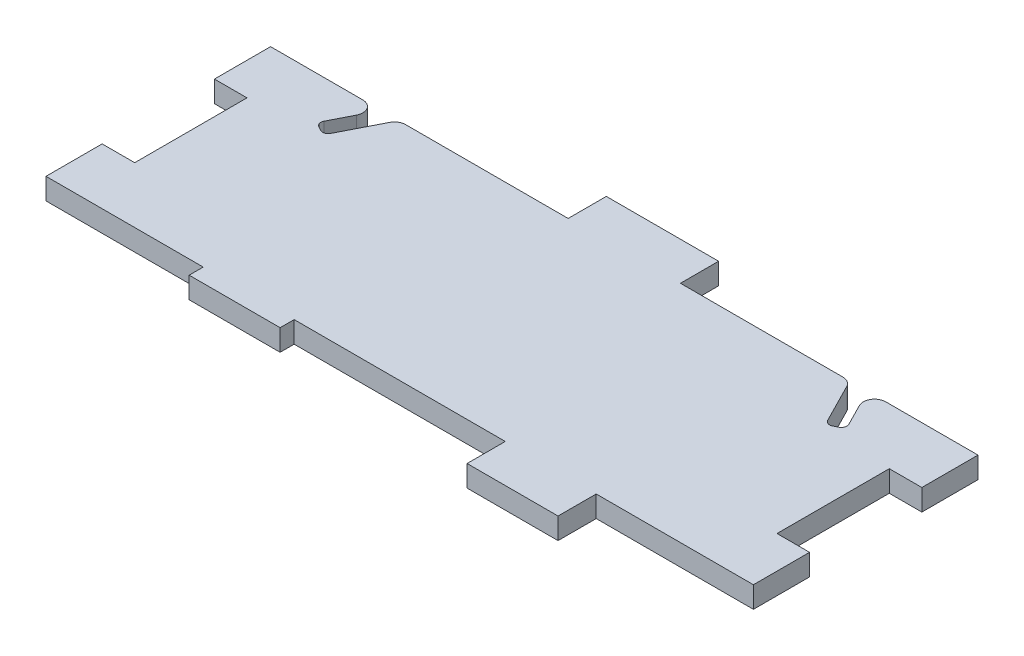
SolidWorks part; units mm, degrees
ref_plane "Front Plane" through (0, 0, 0) normal (0, 0, 1) x (1, 0, 0)
ref_plane "Top Plane" through (0, 0, 0) normal (0, 1, 0) x (1, 0, 0)
ref_plane "Right Plane" through (0, 0, 0) normal (1, 0, 0) x (0, 0, -1)
sketch "Sketch1" plane through (0, 0, 0) normal (0, 1, 0) x (1, 0, 0)
  line L0 (0, -40.8326) -> (0, -51.7928) construction
  line L1 (-80.01, 25.4) -> (-55.0009, 25.4)
  line L2 (-80.01, 25.4) -> (-80.01, 12.7)
  line L3 (-80.01, -25.4) -> (-44.45, -25.4)
  line L4 (80.01, 25.4) -> (80.01, 12.7)
  line L5 (-80.01, 25.4) -> (80.01, -25.4) construction
  line L6 (-80.01, -25.4) -> (80.01, 25.4) construction
  line L8 (-44.45, -25.4) -> (-44.45, -28.575)
  line L9 (-44.45, -28.575) -> (-23.876, -28.575)
  line L10 (-23.876, -25.4) -> (-23.876, -28.575)
  line L11 (23.876, -25.4) -> (23.876, -34.036)
  line L12 (44.45, -34.036) -> (23.876, -34.036)
  line L13 (44.45, -25.4) -> (44.45, -34.036)
  line L14 (-23.876, -25.4) -> (23.876, -25.4)
  line L15 (44.45, -25.4) -> (80.01, -25.4)
  line L16 (80.01, 12.7) -> (72.644, 12.7)
  line L17 (-80.01, 12.7) -> (-72.644, 12.7)
  line L19 (-80.01, -12.7) -> (-72.644, -12.7)
  line L20 (-72.644, 12.7) -> (-72.644, -12.7)
  line L21 (72.644, 12.7) -> (72.644, -12.7)
  line L22 (80.01, -12.7) -> (72.644, -12.7)
  line L23 (-80.01, -12.7) -> (-80.01, -25.4)
  line L24 (80.01, -12.7) -> (80.01, -25.4)
  line L25 (-51.0099, 25.4) -> (-12.7, 25.4)
  line L27 (-55.0009, 25.4) -> (-59.944, 15.6986)
  line L28 (-59.944, 15.6986) -> (-56.7756, 14.0842)
  line L29 (-51.0099, 25.4) -> (-56.7756, 14.0842)
  line L30 (51.0099, 25.4) -> (56.7756, 14.0842)
  line L31 (55.0009, 25.4) -> (59.944, 15.6986)
  line L32 (59.944, 15.6986) -> (56.7756, 14.0842)
  line L33 (55.0009, 25.4) -> (80.01, 25.4)
  line L34 (0, 34.036) -> (0, 23.0758) construction
  line L36 (-12.7, 25.4) -> (-12.7, 34.036)
  line L37 (-12.7, 34.036) -> (12.7, 34.036)
  line L38 (12.7, 25.4) -> (12.7, 34.036)
  line L39 (12.7, 25.4) -> (51.0099, 25.4)
  point P0 (0, 0)
  dimension "D1" = 160.02
  dimension "D2" = 50.8
  dimension "D3" = 35.56
  dimension "D4" = 20.574
  dimension "D5" = 3.175
  dimension "D6" = 12.7
  dimension "D7" = 12.7
  dimension "D8" = 7.366
  dimension "D9" = 3.556
  dimension "D10" = 117
  dimension "D11" = 12.7
  dimension "D12" = 12.7
  dimension "D13" = 25.4
  dimension "D14" = 8.636
  dimension "D15" = 8.636
extrude "Boss-Extrude1" add sketch "Sketch1" along normal blind 4.826
fillet "Fillet1" radius 1.27 4 edges at (-56.7756, 2.413, -14.0842) (-59.944, 2.413, -15.6986) (56.7756, 2.413, -14.0842) (59.944, 2.413, -15.6986)
fillet "Fillet2" radius 2.54 4 edges at (55.0009, 2.413, -25.4) (51.0099, 2.413, -25.4) (-51.0099, 2.413, -25.4) (-55.0009, 2.413, -25.4)
